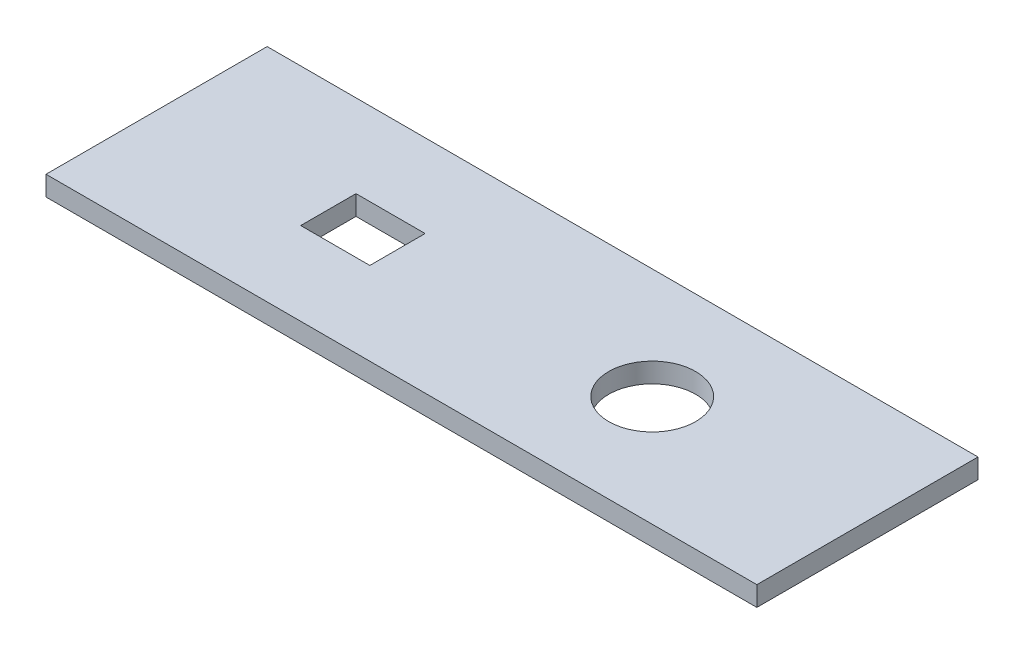
SolidWorks part; units mm, degrees
ref_plane "Ön Düzlem" through (0, 0, 0) normal (0, 0, 1) x (1, 0, 0)
ref_plane "Üst Düzlem" through (0, 0, 0) normal (0, 1, 0) x (1, 0, 0)
ref_plane "Sağ Düzlem" through (0, 0, 0) normal (1, 0, 0) x (0, 0, -1)
sketch "Çizim1" plane through (0, 0, 0) normal (0, 1, 0) x (1, 0, 0)
  line L1 (-90, -28) -> (90, -28)
  line L2 (-90, -28) -> (-90, 28)
  line L3 (-90, 28) -> (90, 28)
  line L4 (90, -28) -> (90, 28)
  line L5 (0, 28) -> (0, -28) construction
  line L6 (-90, 0) -> (90, 0) construction
  line L7 (-46.5, -7) -> (-29, -7)
  line L8 (-46.5, -7) -> (-46.5, 7)
  line L9 (-46.5, 7) -> (-29, 7)
  line L10 (-29, -7) -> (-29, 7)
  line L11 (-37.75, 7) -> (-37.75, -7) construction
  line L12 (-46.5, 0) -> (-29, 0) construction
  circle A0 centre (35.5, 0) radius 11
  point P0 (0, 0)
  point P4 (-37.75, 0)
  dimension "D5" = 22
  dimension "D1" = 180
  dimension "D2" = 56
  dimension "D3" = 17.5
  dimension "D4" = 14
  dimension "D6" = 43.5
  dimension "D7" = 64.5
extrude "Yükseklik-Ekstrüzyon1" add sketch "Çizim1" along normal blind 5
